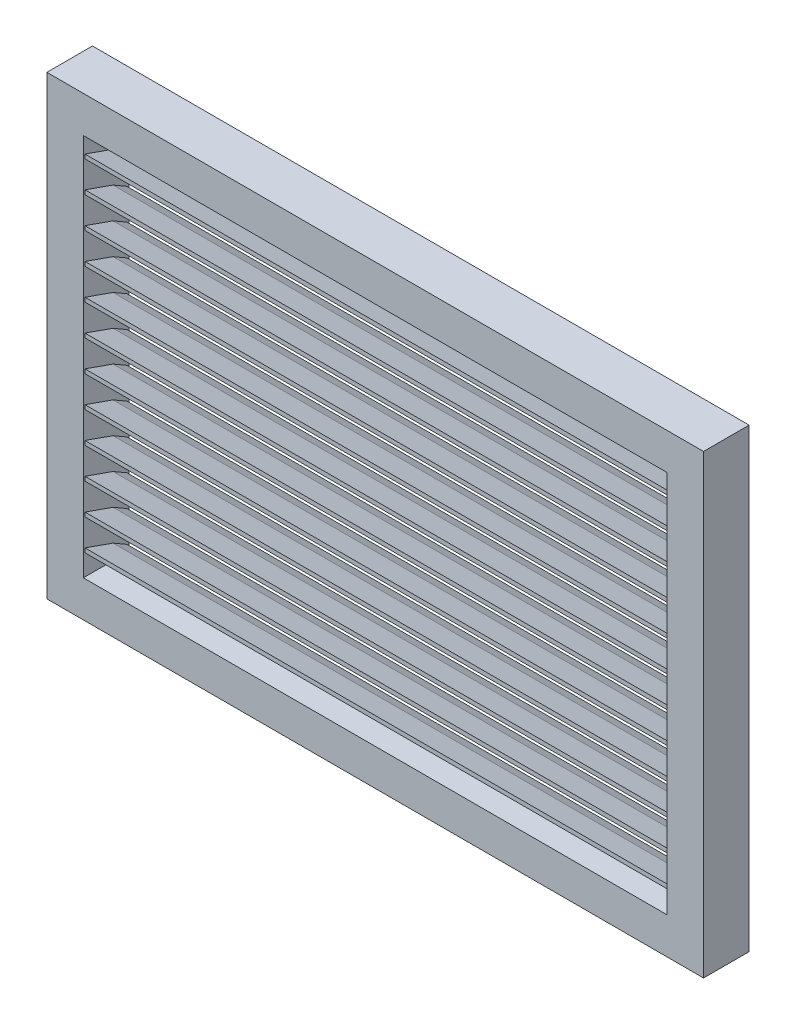
SolidWorks part; units mm, degrees
material "Plain Carbon Steel"
ref_plane "Front Plane" through (0, 0, 0) normal (0, 0, 1) x (1, 0, 0)
ref_plane "Top Plane" through (0, 0, 0) normal (0, 1, 0) x (1, 0, 0)
ref_plane "Right Plane" through (0, 0, 0) normal (1, 0, 0) x (0, 0, -1)
sketch "Sketch1" plane through (0, 0, 0) normal (0, 0, 1) x (1, 0, 0)
  line L1 (0, 0) -> (3600, 0)
  line L2 (0, 0) -> (0, 2500)
  line L3 (0, 2500) -> (3600, 2500)
  line L4 (3600, 0) -> (3600, 2500)
  line L9 (3400, 2300) -> (200, 2300)
  line L10 (3400, 2300) -> (3400, 200)
  line L11 (3400, 200) -> (200, 200)
  line L12 (200, 2300) -> (200, 200)
  dimension "D1" = 3600
  dimension "D2" = 2500
  dimension "D3" = 200
  dimension "D4" = 200
  dimension "D5" = 200
  dimension "D6" = 200
extrude "Boss-Extrude4" add sketch "Sketch1" along normal blind 250 contours L9 L12 L11 L10 | L2 L1 L4 L3
sketch "Sketch2" plane through (3400, 0, 0) normal (-1, 0, 0) x (0, 0, 1)
  line L0 (241.2576, 337.6824) -> (87.5669, 283.536)
  line L1 (87.5669, 283.536) -> (10.7391, 239.1424)
  line L2 (10.7391, 239.1424) -> (20.6527, 221.986)
  line L3 (20.6527, 221.986) -> (87.5669, 260.6512)
  line L4 (87.5669, 260.6512) -> (241.2576, 314.7975)
  line L5 (241.2576, 314.7975) -> (241.2576, 337.6824)
extrude "Boss-Extrude5" add sketch "Sketch2" along normal up to vertex (3200 mm away)
pattern_linear "LPattern1" count 12 spacing 170 along (0, 1, 0) of "Boss-Extrude5"
